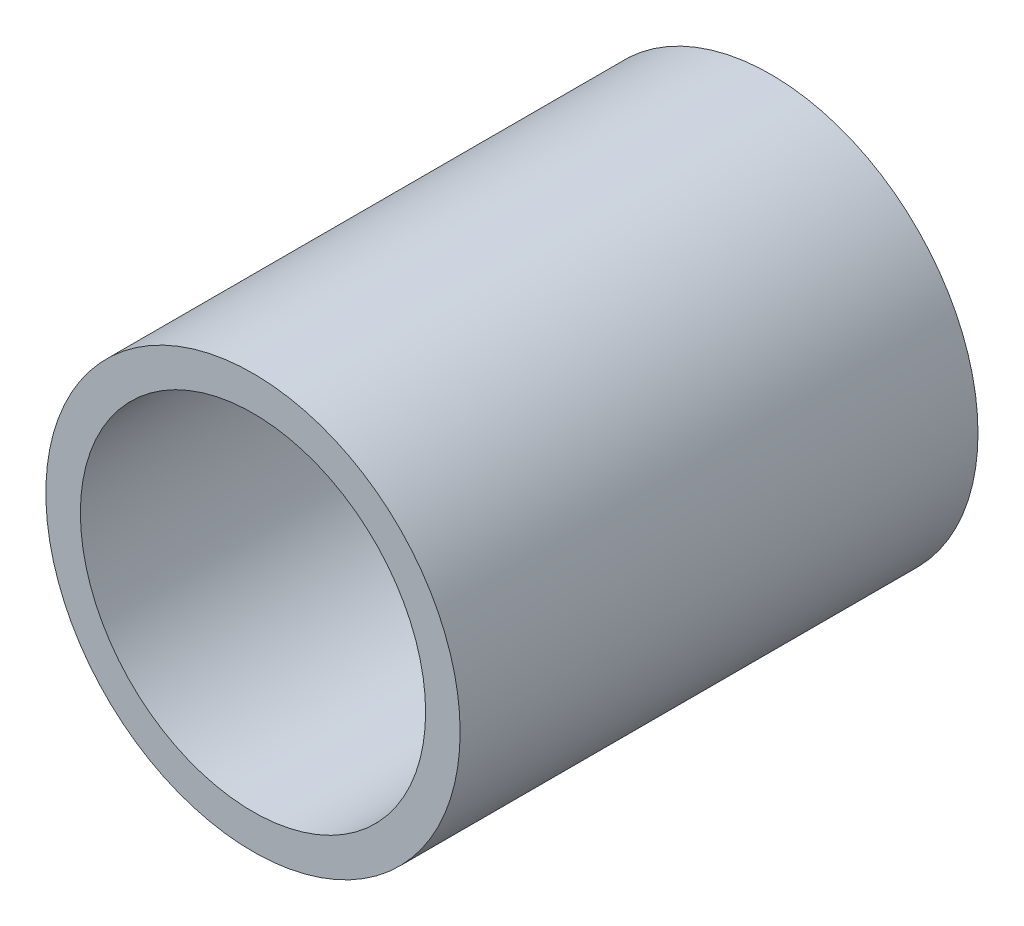
SolidWorks part; units mm, degrees
material "6061-T6 (SS)"
ref_plane "Front Plane" through (0, 0, 0) normal (0, 0, 1) x (1, 0, 0)
ref_plane "Top Plane" through (0, 0, 0) normal (0, 1, 0) x (1, 0, 0)
ref_plane "Right Plane" through (0, 0, 0) normal (1, 0, 0) x (0, 0, -1)
sketch "Sketch1" plane through (0, 0, 0) normal (0, 0, 1) x (1, 0, 0)
  line L1 (7.3323, 0) -> (3.6662, 6.35) construction
  line L2 (3.6662, 6.35) -> (-3.6662, 6.35) construction
  line L3 (-3.6662, 6.35) -> (-7.3323, 0) construction
  line L4 (-7.3323, 0) -> (-3.6662, -6.35) construction
  line L5 (-3.6662, -6.35) -> (3.6662, -6.35) construction
  line L6 (3.6662, -6.35) -> (7.3323, 0) construction
  circle A0 centre (0, 0) radius 6.35 construction
  circle A1 centre (0, 0) radius 7.9375
  circle A2 centre (0, 0) radius 9.525
  dimension "D2" = 15.875
  dimension "D3" = 19.05
  dimension "D1" = 12.7
extrude "Boss-Extrude1" add sketch "Sketch1" along normal blind 23.8125
